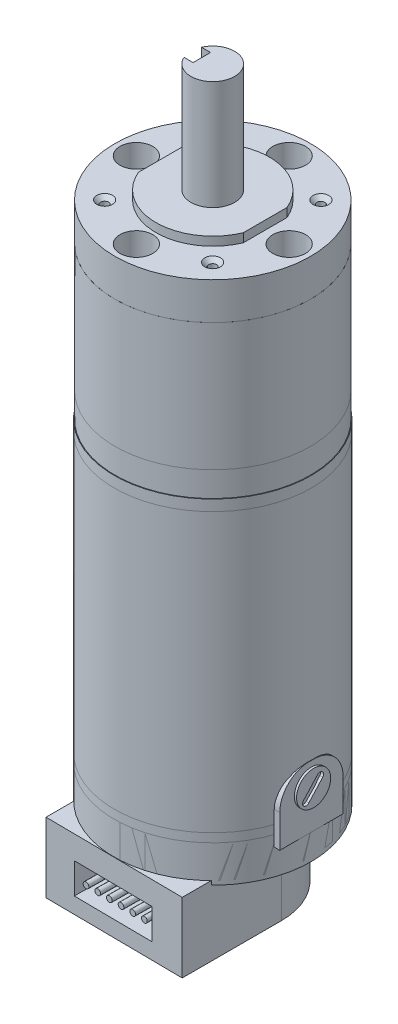
SolidWorks part; units mm, degrees
other "Camera1"
ref_plane "Front Plane" through (0, 0, 0) normal (0, 0, 1) x (1, 0, 0)
ref_plane "Top Plane" through (0, 0, 0) normal (0, 1, 0) x (1, 0, 0)
ref_plane "Right Plane" through (0, 0, 0) normal (1, 0, 0) x (0, 0, -1)
sketch "Sketch1" plane through (0, 0, 0) normal (0, 1, 0) x (1, 0, 0)
  line L0 (0, 45.2965) -> (0, -39.6928) construction
  line L1 (-68.1783, 0) -> (84.9893, 0) construction
  circle A0 centre (0, 0) radius 22.4
  dimension "D1" = 44.8
extrude "Boss-Extrude1" add sketch "Sketch1" along normal blind 8.5
sketch "Sketch2" plane through (0, 0, 0) normal (0, -1, 0) x (1, 0, 0)
  circle A0 centre (0, 0) radius 22.4
  dimension "D1" = 44.8
extrude "Boss-Extrude3" add sketch "Sketch2" along normal blind 29.2 separate body contours A0
sketch "Sketch3" plane through (0, -29.2, 0) normal (0, -1, 0) x (1, 0, 0)
  circle A0 centre (0, 0) radius 22.4
  dimension "D1" = 44.8
extrude "Boss-Extrude4" add sketch "Sketch3" along normal blind 5.7 separate body
sketch "Sketch6" plane through (0, -34.9, 0) normal (0, -1, 0) x (1, 0, 0)
  circle A0 centre (0, 0) radius 22.55
  dimension "D1" = 45.1
extrude "Boss-Extrude5" add sketch "Sketch6" along normal blind 2.5 separate body
sketch "Sketch7" plane through (0, -37.4, 0) normal (0, -1, 0) x (1, 0, 0)
  circle A1 centre (0, 0) radius 22.55
  circle A2 centre (0, 0) radius 22.55
  dimension "D1" = 0
extrude "Boss-Extrude6" add sketch "Sketch7" along normal blind 63.7 separate body
sketch "Sketch8" plane through (0, -101.1, 0) normal (0, -1, 0) x (1, 0, 0)
  circle A1 centre (0, 0) radius 22.55
  circle A2 centre (0, 0) radius 22.55
  dimension "D1" = 0
extrude "Boss-Extrude7" add sketch "Sketch8" along normal blind 2 separate body
sketch "Sketch9" plane through (0, -103.1, 0) normal (0, -1, 0) x (1, 0, 0)
  circle A1 centre (0, 0) radius 22.55
  circle A2 centre (0, 0) radius 22.55
  dimension "D1" = 0
extrude "Boss-Extrude8" add sketch "Sketch9" along normal blind 8.4 separate body
sketch "Sketch10" plane through (0, 8.5, 0) normal (0, 1, 0) x (1, 0, 0)
  circle A0 centre (0, 0) radius 13
  dimension "D1" = 26
extrude "Boss-Extrude9" add sketch "Sketch10" along normal blind 2
sketch "Sketch17" plane through (0, -103.1, 0) normal (0, -1, 0) x (1, 0, 0)
  circle A1 centre (0, 0) radius 22.55
  circle A2 centre (0, 0) radius 22.55
  dimension "D1" = 0
extrude "Boss-Extrude11" add sketch "Sketch17" along normal blind 7.5 separate body
sketch "Sketch11" plane through (0, 10.5, 0) normal (0, 1, 0) x (1, 0, 0)
  circle A0 centre (0, 0) radius 5
  dimension "D1" = 10
extrude "Boss-Extrude10" add sketch "Sketch11" along normal blind 25 separate body
sketch "Sketch12" plane through (0, 0, 0) normal (1, 0, 0) x (0, 0, -1)
  line L0 (0, 40.7439) -> (0, 7.765) construction
  line L1 (0, 17.5) -> (0, 38.9391) construction
  line L2 (-2, 17.5) -> (-2, 38.9391)
  line L3 (2, 17.5) -> (2, 38.9391)
  line L4 (5, 35.5) -> (-5, 35.5) construction
  arc A0 (-2, 17.5) -> (2, 17.5) centre (0, 17.5) ccw
  arc A1 (2, 38.9391) -> (-2, 38.9391) centre (0, 38.9391) ccw
  point P5 (0, 28.2195)
  dimension "D1" = 2
  dimension "D2" = 18
extrude "Cut-Extrude1" cut sketch "Sketch12" against normal offset from surface (5.246 mm away) 3 from offset 2.5 offset against normal yes
sketch "Sketch13" plane through (0, 8.5, 0) normal (0, 1, 0) x (1, 0, 0)
  circle A0 centre (0, 0) radius 17.5 construction
  circle A1 centre (0, 17.5) radius 3.75
  circle A2 centre (17.5, 0) radius 3.75
  circle A3 centre (0, -17.5) radius 3.75
  circle A4 centre (-17.5, 0) radius 3.75
  point P14 (0, 0)
  dimension "D1" = 35
  dimension "D3" = 7.5
  dimension "D2" = 4
extrude "Cut-Extrude2" cut sketch "Sketch13" against normal blind 15
hole_wizard "CSK for M1.6 Countersunk Flat Head Screw1" positions "3DSketch1" profile "Sketch14" countersink size "M1.6" standard "DIN"
sketch3d "3DSketch1"
  line L0 (0, 0, 0) -> (-33.2873, 0, 0) construction
  line L2 (0, 0, 0) -> (0, 0, -24.9963) construction
  line L4 (-12.3744, 0, -12.3744) -> (0, 0, 0) construction
  circle A0 centre (0, 0, 0) radius 17.5 construction
  point P0 (-12.3673, 8.5, -12.3975)
  point P6 (0, 17.5, 0)
  dimension "D1" = 35
  dimension "D2" = 45
sketch "Sketch14" plane through (-12.3673, 8.5, -12.3975) normal (1, 0, 0) x (0, 0, 1)
  line L0 (0, 0) -> (0, 15.5408)
  line L1 (0, 15.5408) -> (0.9, 15)
  line L2 (0.9, 15) -> (0.9, 0.9)
  line L3 (0.9, 0.9) -> (1.8, 0)
  line L5 (1.8, 0) -> (0, 0)
  line L6 (-0.9, 0.9) -> (-1.8, 0) construction
  line L10 (0, 15.5408) -> (-0.9, 15) construction
  line L11 (0, -6.35) -> (0, 107.95) construction
  dimension "Hole Dia." = 1.8
  dimension "Hole Depth" = 15
  dimension "Near C'Sink Dia." = 3.6
  dimension "Near C'Sink Angle" = 90
  dimension "Drill Angle" = 118
pattern_circular "CirPattern1" count 4 over 360 about axis through (0, 0, 0) along (0, 1, 0) of "CSK for M1.6 Countersunk Flat Head Screw1"
sketch "Sketch15" plane through (0, 10.5, 0) normal (0, 1, 0) x (1, 0, 0)
  line L0 (0, 27.2608) -> (0, 13) construction
  line L1 (-12, 5) -> (-12, -5)
  line L2 (12, 5) -> (12, -5)
  line L4 (0, -13) -> (0, -27.2352) construction
  circle A1 centre (0, 0) radius 13
  arc A2 (-12, 5) -> (-12, -5) centre (0, 0) ccw
  arc A3 (-4.5826, -2) -> (-4.5826, 2) centre (0, 0) ccw construction
  arc A4 (-4.5826, -2) -> (0, -5) centre (0, 0) ccw
  arc A5 (12, -5) -> (12, 5) centre (0, 0) ccw
  dimension "D2" = 24
  dimension "D1" = 0
extrude "Cut-Extrude4" cut sketch "Sketch15" against normal up to surface (2 mm away) contours A5 L2 | A2 L1 up to face at (-10.5975, 8.5, 12.3673)
ref_plane "Plane1" through (22.6, 0, 0) normal (1, 0, 0) x (0, 0, -1)
ref_plane "Plane2" through (-22.6, 0, 0) normal (1, 0, 0) x (0, 0, -1)
sketch "Sketch16" plane through (22.6, 0, 0) normal (1, 0, 0) x (0, 0, -1)
  line L0 (0, -88.1388) -> (0, -91.6456) construction
  line L2 (-7.25, -105.6) -> (-7.25, -98.1)
  line L3 (-7.25, -105.6) -> (7.25, -105.6)
  line L4 (-22.55, -110.6) -> (22.55, -110.6) construction
  line L6 (7.25, -105.6) -> (7.25, -98.1)
  line L7 (0, -105.6) -> (0, -108.2954) construction
  arc A1 (-7.25, -98.1) -> (0, -91.4) centre (-0.5291, -98.1) cw
  arc A2 (7.25, -98.1) -> (0, -91.4) centre (0.5291, -98.1) ccw
  dimension "D2" = 14.5
  dimension "D3" = 5
  dimension "D4" = 14.2
extrude "Boss-Extrude12" add sketch "Sketch16" along direction (1, 0, 0) on the side against the normal up to surface (45.2 mm away) separate body up to plane "Plane2"
sketch "Sketch18" plane through (22.6, 0, 0) normal (1, 0, 0) x (0, 0, -1)
  line L0 (1.477, -94.4815) -> (-1.2887, -98.4722) construction
  line L1 (1.9621, -94.8177) -> (-0.8036, -98.8083)
  line L2 (0.992, -94.1454) -> (-1.7737, -98.136)
  circle A0 centre (0, -96.6127) radius 3.9084
  arc A1 (1.9621, -94.8177) -> (0.992, -94.1454) centre (1.477, -94.4815) ccw
  arc A2 (-1.7737, -98.136) -> (-0.8036, -98.8083) centre (-1.2887, -98.4722) ccw
  point P4 (0.0942, -96.4768)
extrude "Boss-Extrude13" add sketch "Sketch18" along normal blind 0.5 contours A0
sketch "Sketch19" plane through (23.1, 0, 0) normal (1, 0, 0) x (0, 0, -1)
  line L0 (1.4964, -94.9756) -> (-1.7124, -98.4862) construction
  line L1 (2.0927, -95.5207) -> (-1.1161, -99.0312)
  line L2 (0.9001, -94.4306) -> (-2.3087, -97.9411)
  arc A0 (2.0927, -95.5207) -> (0.9001, -94.4306) centre (1.4964, -94.9756) ccw
  arc A1 (-2.3087, -97.9411) -> (-1.1161, -99.0312) centre (-1.7124, -98.4862) ccw
  point P2 (-0.108, -96.7309)
extrude "Cut-Extrude5" cut sketch "Sketch19" against normal blind 2
mirror "Mirror25" about plane through (0, 0, 0) normal (1, 0, 0) of "Boss-Extrude13", "Cut-Extrude5"
sketch "Sketch21" plane through (0, -110.6, 0) normal (0, -1, 0) x (1, 0, 0)
  line L0 (-15.75, 0) -> (-15.75, 22.4412)
  line L1 (-15.75, 22.4412) -> (15.75, 22.7483)
  line L2 (15.75, 22.7483) -> (15.75, 0)
  arc A0 (-15.75, 0) -> (15.75, 0) centre (0, 0) ccw
  dimension "D1" = 31.5
extrude "Boss-Extrude15" add sketch "Sketch21" along normal blind 16 separate body
sketch "Sketch22" plane through (-0.2203, 0, 22.5926) normal (-0.0097, 0, 1) x (1, 0, 0.0097)
  line L0 (0, -96.6697) -> (0, -130.0506) construction
  line L2 (-9, -115.9366) -> (9, -115.9366)
  line L3 (-9, -115.9366) -> (-9, -122.9366)
  line L4 (-9, -122.9366) -> (9, -122.9366)
  line L5 (9, -115.9366) -> (9, -122.9366)
  dimension "D1" = 7
  dimension "D2" = 18
extrude "Cut-Extrude6" cut sketch "Sketch22" against normal blind 16
sketch "Sketch23" plane through (-0.0643, 0, 6.5934) normal (-0.0097, 0, 1) x (1, 0, 0.0097)
  line L0 (-9, -119.4366) -> (10.1922, -119.4366) construction
  line L1 (-9, -115.9366) -> (-9, -122.9366) construction
  circle A0 centre (7.22, -119.4366) radius 0.6637
  circle A1 centre (4.52, -119.4366) radius 0.6637
  circle A2 centre (1.82, -119.4366) radius 0.6637
  circle A3 centre (-0.88, -119.4366) radius 0.6637
  circle A4 centre (-3.58, -119.4366) radius 0.6637
  circle A5 centre (-6.28, -119.4366) radius 0.6637
  dimension "D1" = 6
extrude "Boss-Extrude16" add sketch "Sketch23" along normal blind 16
equation "\"ىى\"=2.5"
